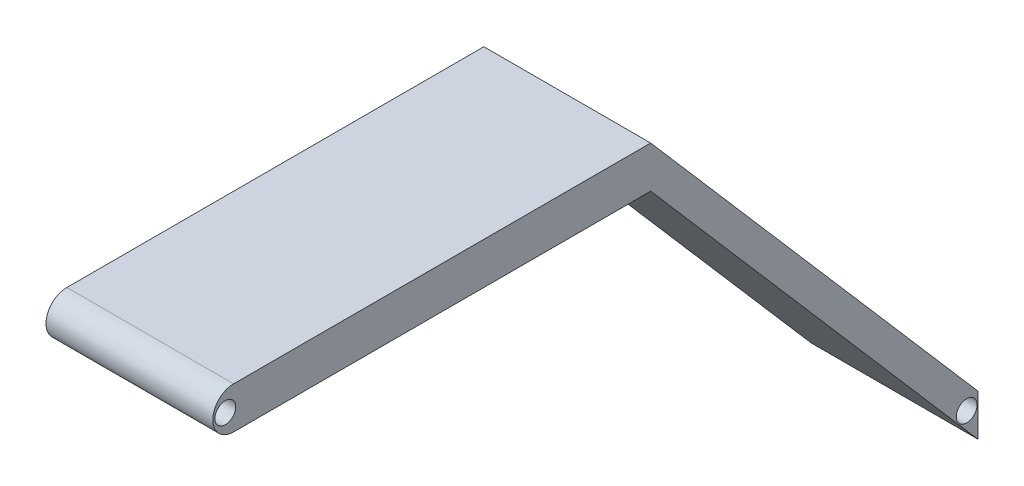
SolidWorks part; units mm, degrees
ref_plane "前视基准面" through (0, 0, 0) normal (0, 0, 1) x (1, 0, 0)
ref_plane "上视基准面" through (0, 0, 0) normal (0, 1, 0) x (1, 0, 0)
ref_plane "右视基准面" through (0, 0, 0) normal (1, 0, 0) x (0, 0, -1)
other "Configuration Table"
sketch "草图1" plane through (0, 0, 0) normal (1, 0, 0) x (0, 0, -1)
  line L1 (-11.1742, 5.6744) -> (-1.1742, 5.6744)
  line L2 (-11.1742, 5.6744) -> (-11.1742, 4.6744)
  line L3 (-11.1742, 4.6744) -> (-1.1742, 4.6744)
  line L4 (-1.1742, 5.6744) -> (-1.1742, 4.6744)
  line L5 (-11.1742, 5.6744) -> (-1.1742, 4.6744) construction
  line L6 (-11.1742, 4.6744) -> (-1.1742, 5.6744) construction
  point P0 (-6.1742, 5.1744)
  dimension "D1" = 10
  dimension "D2" = 1
extrude "凸台-拉伸1" add sketch "草图1" along normal blind 4
sketch "草图3" plane through (4, 0, 0) normal (1, 0, 0) x (0, 0, -1)
  line L3 (8.0183, 12.3878) -> (8.0183, 13.3878)
sketch "草图4" plane through (4, 0, 0) normal (1, 0, 0) x (0, 0, -1)
  line L0 (-1.1742, 5.6744) -> (-1.1742, 4.6744)
  line L1 (-1.1742, 5.6744) -> (6.6751, -3.4024)
  line L2 (-1.1742, 4.6744) -> (6.6751, -4.4024)
  line L3 (6.6751, -3.4024) -> (6.6751, -4.4024)
  dimension "D1" = 12
extrude "凸台-拉伸2" add sketch "草图4" against normal blind 4
sketch "草图7" plane through (4, 0, 0) normal (1, 0, 0) x (0, 0, -1)
  line L0 (-11.1742, 5.6744) -> (-11.1742, 4.6744)
  arc A0 (-11.1742, 4.6744) -> (-11.1742, 5.6744) centre (-11.1742, 5.1744) cw
extrude "凸台-拉伸4" add sketch "草图7" against normal up to vertex (4 mm away)
sketch "草图8" plane through (4, 0, 0) normal (1, 0, 0) x (0, 0, -1)
  circle A0 centre (-11.3742, 5.1744) radius 0.25
  arc A1 (-11.1742, 5.6744) -> (-11.1742, 4.6744) centre (-11.1742, 5.1744) ccw construction
  dimension "D1" = 0.5
  dimension "D2" = 0.2
extrude "切除-拉伸1" cut sketch "草图8" against normal blind 10
sketch "草图9" plane through (4, 0, 0) normal (1, 0, 0) x (0, 0, -1)
  line L0 (-1.1742, 4.6744) -> (6.6751, -4.4024) construction
  circle A0 centre (6.4037, -3.6758) radius 0.25
  dimension "D1" = 0.5
  dimension "D2" = 0.27
extrude "切除-拉伸2" cut sketch "草图9" against normal blind 10
scale "缩放比例1" scale about centroid uniform scaling yes scale factor 2.454545
